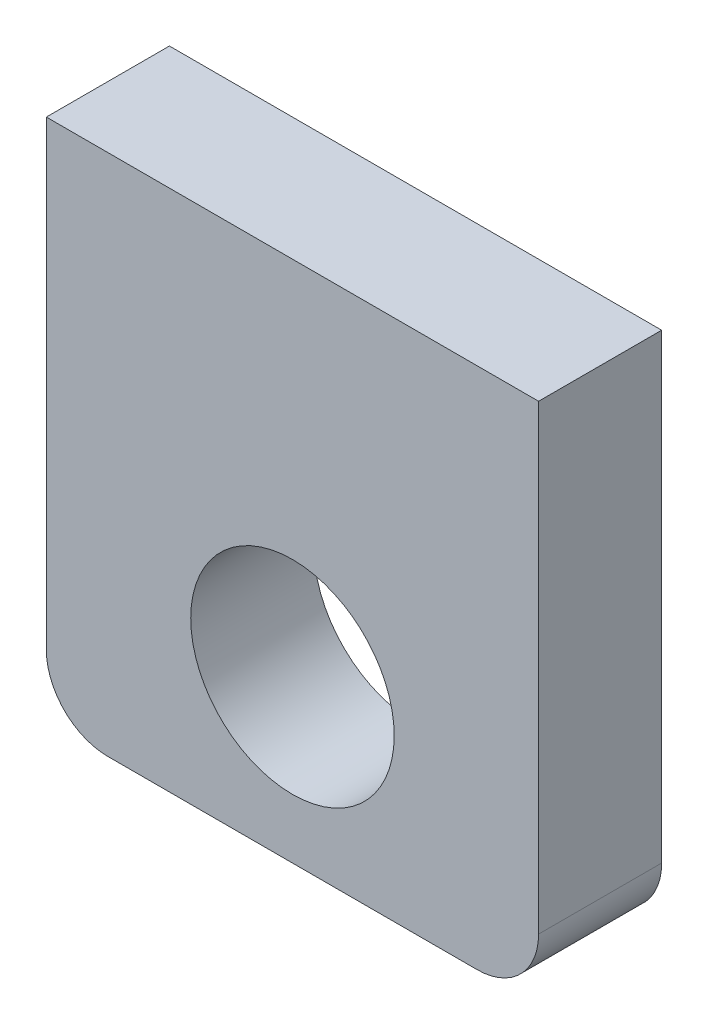
SolidWorks part; units mm, degrees
material "Oak"
ref_plane "Front Plane" through (0, 0, 0) normal (0, 0, 1) x (1, 0, 0)
ref_plane "Top Plane" through (0, 0, 0) normal (0, 1, 0) x (1, 0, 0)
ref_plane "Right Plane" through (0, 0, 0) normal (1, 0, 0) x (0, 0, -1)
sketch "Sketch1" plane through (0, 0, 0) normal (0, 0, 1) x (1, 0, 0)
  line L1 (-25.4, -26.9875) -> (25.4, -26.9875)
  line L2 (-25.4, -26.9875) -> (-25.4, 26.9875)
  line L3 (-25.4, 26.9875) -> (25.4, 26.9875)
  line L4 (25.4, -26.9875) -> (25.4, 26.9875)
  line L5 (-25.4, -26.9875) -> (25.4, 26.9875) construction
  line L6 (-25.4, 26.9875) -> (25.4, -26.9875) construction
  point P0 (0, 0)
  dimension "D1" = 50.8
  dimension "D2" = 53.975
extrude "Boss-Extrude1" add sketch "Sketch1" along normal mid plane 12.7
sketch "Sketch2" plane through (0, 0, 6.35) normal (0, 0, 1) x (1, 0, 0)
  line L0 (25.4, 26.9875) -> (-25.4, 26.9875) construction
  circle A0 centre (0, -10.3505) radius 10.5
  dimension "D1" = 21
  dimension "D2" = 37.338
extrude "Cut-Extrude1" cut sketch "Sketch2" against normal through all and the other way through all
fillet "Fillet1" radius 6.35 2 edges at (25.4, -26.9875, 0) (-25.4, -26.9875, 0)
sketch "Sketch3" [suppressed] plane through (0, 0, 2.5) normal (0, 0, 1) x (1, 0, 0)
  line L0 (25.4, 25.019) -> (-25.4, 25.019) construction
  line L1 (0, -5.319) -> (0, 10.181) construction
  line L2 (0, -5.319) -> (7.75, 8.1044) construction
  circle A0 centre (0, -12.319) radius 6.35
  circle A1 centre (0, -5.319) radius 15.5 construction
  circle A2 centre (7.75, 8.1044) radius 2.3813
  circle A3 centre (15.5, -5.319) radius 2.3813
  circle A4 centre (7.75, -18.7424) radius 2.3813
  circle A5 centre (-7.75, -18.7424) radius 2.3813
  circle A6 centre (-15.5, -5.319) radius 2.3812
  circle A7 centre (-7.75, 8.1044) radius 2.3813
  point P23 (0, -5.319)
  dimension "D1" = 12.7
  dimension "D3" = 31
  dimension "D5" = 4.7625
  dimension "D2" = 37.338
  dimension "D4" = 30.338
  dimension "D6" = 30
  dimension "D8" = 13.4234
  dimension "D7" = 6
extrude "Cut-Extrude2" [suppressed] cut sketch "Sketch3" against normal through all
